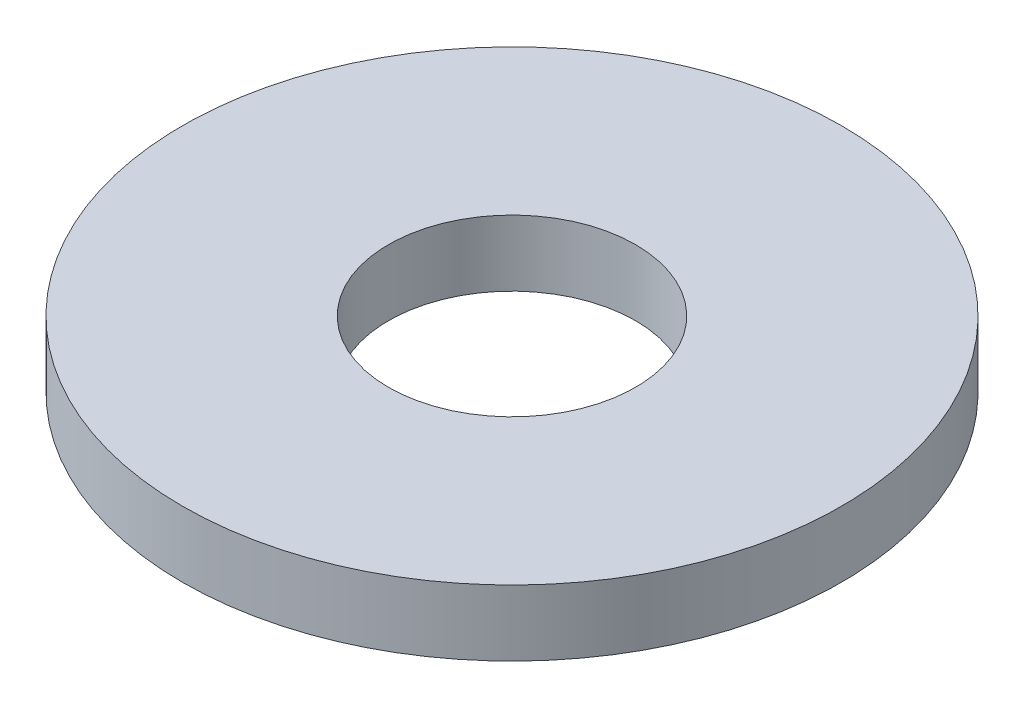
SolidWorks part; units mm, degrees
ref_plane "Front Plane" through (0, 0, 0) normal (0, 0, 1) x (1, 0, 0)
ref_plane "Top Plane" through (0, 0, 0) normal (0, 1, 0) x (1, 0, 0)
ref_plane "Right Plane" through (0, 0, 0) normal (1, 0, 0) x (0, 0, -1)
sketch "Sketch1" plane through (0, 0, 0) normal (0, 1, 0) x (1, 0, 0)
  circle A0 centre (0, 0) radius 25.4
  dimension "D1" = 50.8
extrude "Boss-Extrude1" add sketch "Sketch1" along normal blind 5.08
sketch "Sketch2" plane through (0, 5.08, 0) normal (0, 1, 0) x (1, 0, 0)
  circle A0 centre (0, 0) radius 9.525
  dimension "D1" = 19.05
extrude "Cut-Extrude1" cut sketch "Sketch2" against normal blind 5.08
